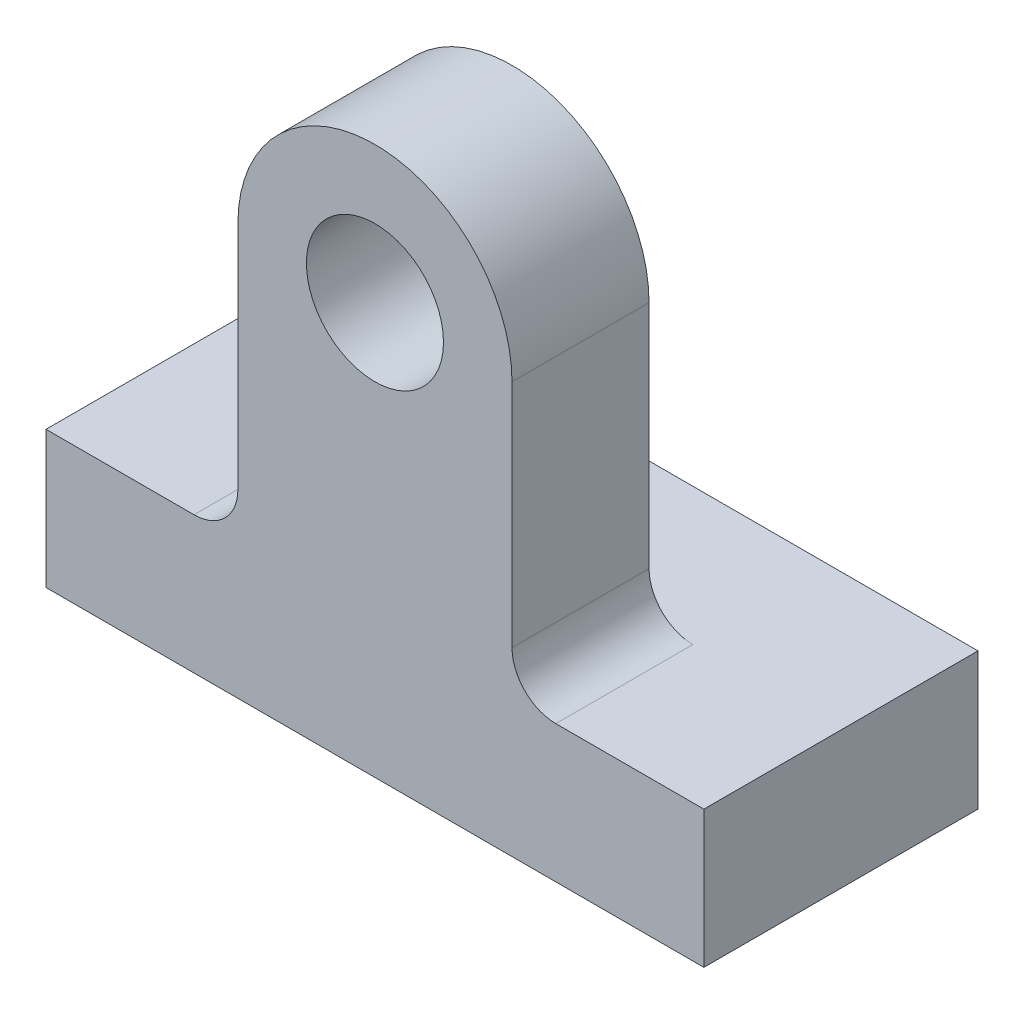
SolidWorks part; units mm, degrees
ref_plane "Front Plane" through (0, 0, 0) normal (0, 0, 1) x (1, 0, 0)
ref_plane "Top Plane" through (0, 0, 0) normal (0, 1, 0) x (1, 0, 0)
ref_plane "Right Plane" through (0, 0, 0) normal (1, 0, 0) x (0, 0, -1)
sketch "Rectangle Sketch" plane through (0, 0, 0) normal (0, 1, 0) x (1, 0, 0)
  line L1 (0, 0) -> (3048, 0)
  line L2 (0, 0) -> (0, -1270)
  line L3 (0, -1270) -> (3048, -1270)
  line L4 (3048, 0) -> (3048, -1270)
  dimension "D1" = 1270
  dimension "D2" = 3048
extrude "RectangleExtrude" add sketch "Rectangle Sketch" along normal blind 635
sketch "CurvedRectangleSketch" plane through (0, 0, 1270) normal (0, 0, 1) x (1, 0, 0)
  line L0 (889, 635) -> (889, 1905)
  line L1 (0, 635) -> (3048, 635) construction
  line L2 (2159, 635) -> (2159, 1905)
  line L3 (889, 635) -> (2159, 635)
  arc A0 (889, 1905) -> (2159, 1905) centre (1524, 1905) cw
  circle A1 centre (1524, 1905) radius 317.5
  point P8 (0, 0)
  dimension "D1" = 635
  dimension "D3" = 1270
  dimension "D2" = 889
extrude "CurvedRectangleExtrude" add sketch "CurvedRectangleSketch" against normal blind 635 contours A0 L2 L3 L0 | A1
fillet "CurvedRectangleFillet" radius 203.2 2 edges at (2159, 635, 952.5) (889, 635, 952.5)
